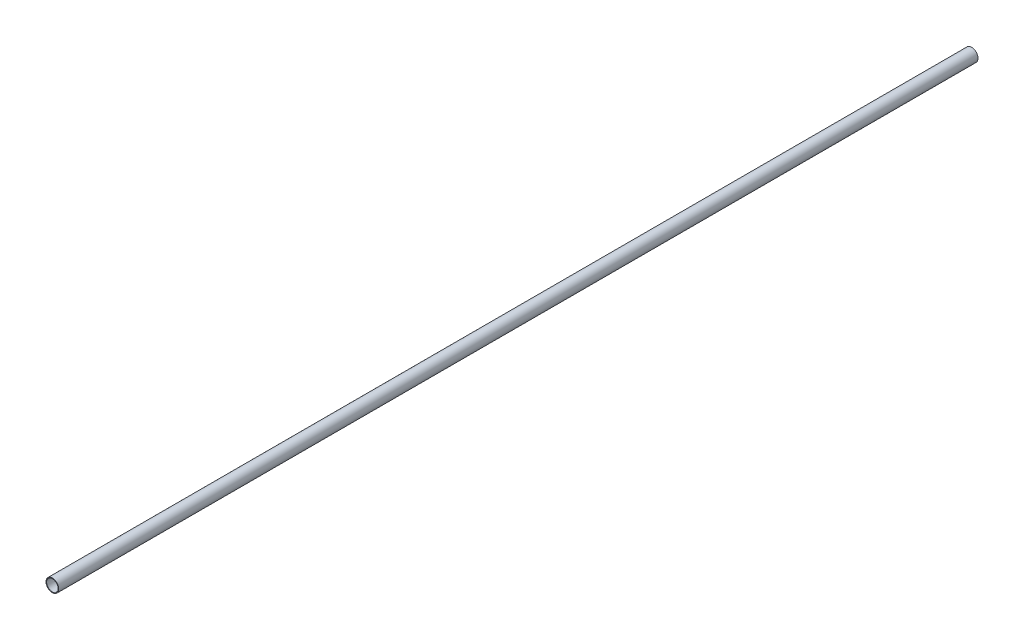
SolidWorks part; units mm, degrees
ref_plane "Front Plane" through (0, 0, 0) normal (0, 0, 1) x (1, 0, 0)
ref_plane "Top Plane" through (0, 0, 0) normal (0, 1, 0) x (1, 0, 0)
ref_plane "Right Plane" through (0, 0, 0) normal (1, 0, 0) x (0, 0, -1)
sketch "Sketch1" plane through (0, 0, 0) normal (0, 0, 1) x (1, 0, 0)
  line L0 (12.7, 0) -> (-12.7, 0) construction
  line L1 (0, -11.4554) -> (0, 11.4554) construction
  line L2 (0, -12.7) -> (0, 12.7) construction
  circle A0 centre (0, 0) radius 12.7 construction
  circle A1 centre (0, 0) radius 11.4554 construction
  point P6 (0, 0)
  point P7 (-11.4554, 0)
  point P8 (11.4554, 0)
  point P10 (-12.7, 0)
  point P11 (12.7, 0)
  point P14 (0, 0)
  point P17 (0, 0)
  point P18 (0, 11.4554)
  point P19 (0, 12.7)
  point P20 (0, -11.4554)
  point P21 (0, -12.7)
  dimension "OD" = 25.4
  dimension "ID" = 22.9108
  dimension "Wall Thickness" = 1.2446
sketch "Sketch2" plane through (0, 0, 0) normal (1, 0, 0) x (0, 0, -1)
  line L0 (0, -11.4554) -> (0, 11.4554) construction
  line L1 (0, -11.4554) -> (0, 11.4554) construction
  line L2 (0, -12.7) -> (0, 12.7) construction
  line L3 (0, -12.7) -> (0, 12.7) construction
  line L4 (914.4, 12.7) -> (-914.4, 12.7) construction
  line L5 (914.4, 11.4554) -> (-914.4, 11.4554) construction
  line L6 (914.4, -11.4554) -> (-914.4, -11.4554) construction
  line L7 (914.4, -12.7) -> (-914.4, -12.7) construction
  line L8 (-914.4, -12.7) -> (-914.4, 12.7) construction
  line L9 (914.4, 12.7) -> (914.4, -12.7) construction
  line L10 (914.4, 0) -> (-914.4, 0) construction
  line L11 (-903.1111, -12.7) -> (-903.1111, 12.7) construction
  line L12 (903.1111, -12.7) -> (903.1111, 12.7) construction
  point P7 (0, 12.7)
  point P10 (0, 11.4554)
  point P13 (0, -11.4554)
  point P16 (0, -12.7)
  point P17 (-914.4, -12.7)
  point P18 (-914.4, -11.4554)
  point P19 (-914.4, 11.4554)
  point P20 (-914.4, 12.7)
  point P21 (914.4, 12.7)
  point P22 (914.4, 11.4554)
  point P23 (914.4, -11.4554)
  point P24 (914.4, -12.7)
  point P28 (0, 0)
  point P30 (-903.1111, 0)
  point P31 (-903.1111, -12.7)
  point P32 (-903.1111, 12.7)
  point P35 (903.1111, 0)
  point P36 (903.1111, 12.7)
  point P37 (903.1111, -12.7)
  dimension "Length" = 1828.8
  dimension "Break Line" = 11.2889
sketch "Sketch3" plane through (0, 0, 0) normal (0, 0, 1) x (1, 0, 0)
  circle A0 centre (0, 0) radius 11.4554 construction
  circle A1 centre (0, 0) radius 12.7 construction
  circle A2 centre (0, 0) radius 11.4554
  circle A3 centre (0, 0) radius 12.7
extrude "Boss-Extrude1" add sketch "Sketch3" along normal up to vertex (914.4 mm away) and the other way up to vertex (914.4 mm away) up to point (0, 0, 914.4) other way up to point (0, 0, -914.4)
equation "\"Break Line@Sketch2\"=\"OD@Sketch1\"/2.25"
